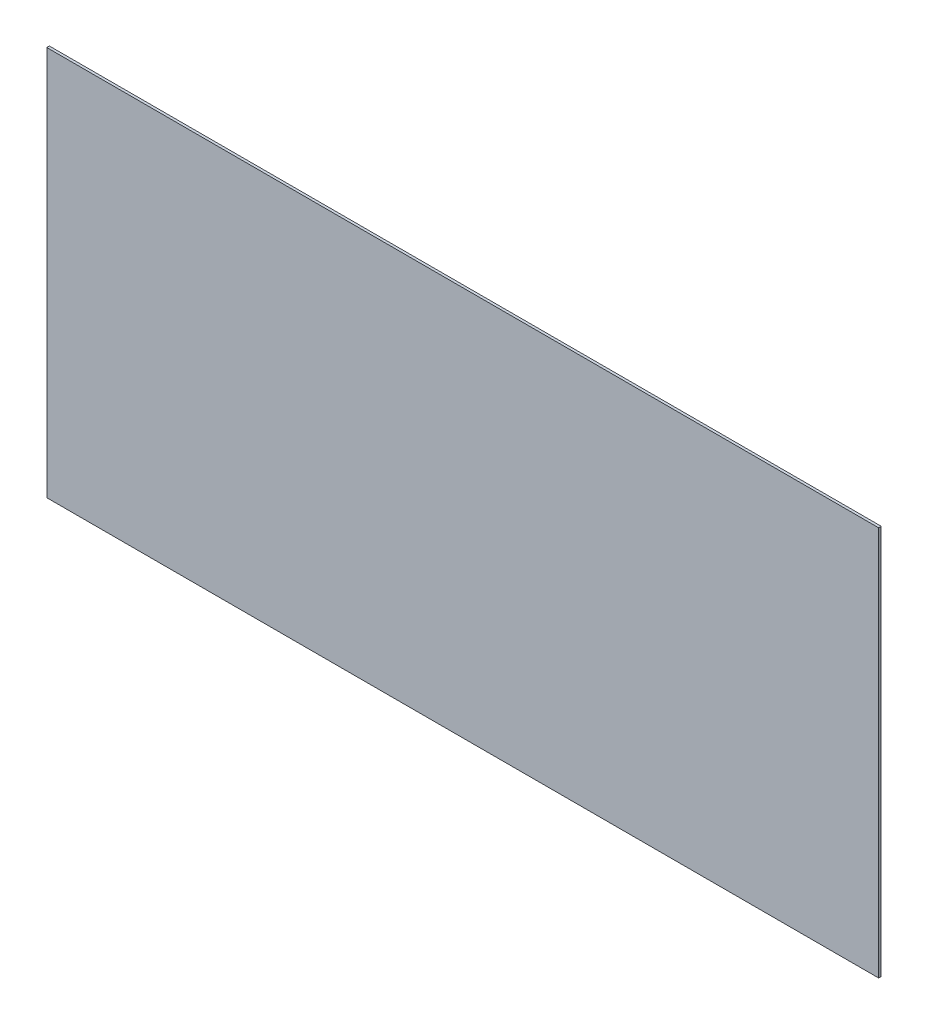
SolidWorks part; units mm, degrees
ref_plane "Front Plane" through (0, 0, 0) normal (0, 0, 1) x (1, 0, 0)
ref_plane "Top Plane" through (0, 0, 0) normal (0, 1, 0) x (1, 0, 0)
ref_plane "Right Plane" through (0, 0, 0) normal (1, 0, 0) x (0, 0, -1)
sketch "Sketch1" plane through (0, 0, 0) normal (0, 0, 1) x (1, 0, 0)
  line L1 (0, 0) -> (640, 0)
  line L2 (0, 0) -> (0, -300)
  line L3 (0, -300) -> (640, -300)
  line L4 (640, 0) -> (640, -300)
  circle A0 centre (512.1092, -140) radius 50 construction
  dimension "D5" = 100
  dimension "D1" = 640
  dimension "D2" = 300
  dimension "D3" = 127.8908
  dimension "D4" = 140
extrude "Boss-Extrude1" add sketch "Sketch1" along normal blind 2
